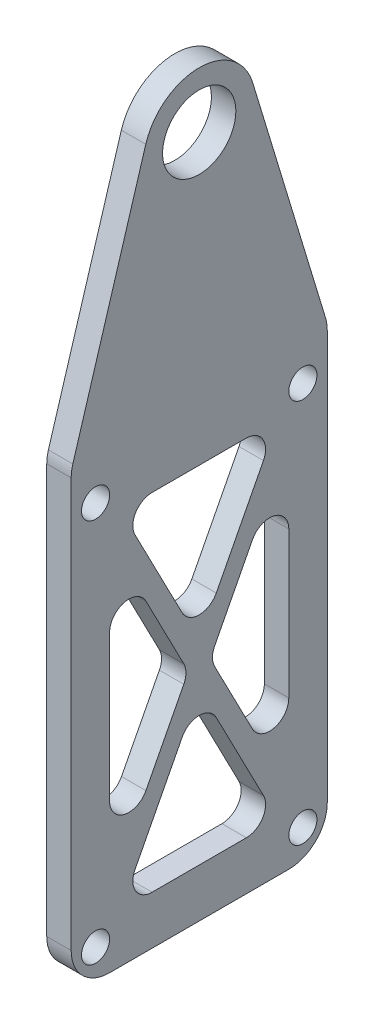
SolidWorks part; units mm, degrees
material "6061 Alloy"
ref_plane "Front Plane" through (0, 0, 0) normal (0, 0, 1) x (1, 0, 0)
ref_plane "Top Plane" through (0, 0, 0) normal (0, 1, 0) x (1, 0, 0)
ref_plane "Right Plane" through (0, 0, 0) normal (1, 0, 0) x (0, 0, -1)
sketch "Sketch1" plane through (0, 0, 0) normal (1, 0, 0) x (0, 0, -1)
  line L0 (-13.4747, 0) -> (13.4747, 0) construction
  line L1 (0, 0) -> (0, 35) construction
  line L2 (-13.4747, 0) -> (0, 35) construction
  line L3 (0, 35) -> (13.4747, 0) construction
  line L4 (13.4747, 0) -> (-13.4747, 0) construction
  line L8 (-13.4747, 0) -> (13.4747, 0) construction
  line L9 (-13.4747, 0) -> (-13.4747, -50) construction
  line L10 (13.4747, 0) -> (13.4747, -50) construction
  line L11 (-13.4747, -50) -> (13.4747, -50) construction
  line L16 (-16.645, -53.81) -> (16.645, -53.81)
  line L17 (-16.645, -53.81) -> (-16.645, 5.15)
  line L18 (16.645, -53.81) -> (16.645, 5.15)
  line L19 (-16.645, 5.15) -> (16.645, 5.15)
  line L20 (-16.645, 5.15) -> (-6.9497, 37.1084)
  line L21 (-6.9497, 37.1084) -> (6.9497, 37.1084) construction
  line L22 (6.9497, 37.1084) -> (16.645, 5.15)
  circle A0 centre (-13.4747, 0) radius 1.8288
  circle A1 centre (0, 35) radius 4.7625
  circle A2 centre (13.4747, 0) radius 1.8288
  circle A3 centre (-13.4747, -50) radius 1.8288
  circle A4 centre (13.4747, -50) radius 1.8288
  arc A5 (-6.9497, 37.1084) -> (6.9497, 37.1084) centre (0, 35) cw
  point P4 (0, 0)
  point P7 (0, -53.81)
  dimension "D3" = 3.6576
  dimension "D4" = 9.525
  dimension "D9" = 2.5
  dimension "D1" = 26.9494
  dimension "D5" = 50
  dimension "D6" = 3.81
  dimension "D7" = 35
  dimension "D8" = 5.15
  dimension "D2" = 33.29
extrude "Boss-Extrude1" add sketch "Sketch1" along normal blind 3.175
sketch "Sketch2" plane through (3.175, 0, 0) normal (1, 0, 0) x (0, 0, -1)
  line L3 (-11.645, -47.5) -> (-11.645, -2.5)
  line L4 (11.645, -47.5) -> (11.645, -2.5)
  line L5 (-11.645, -2.5) -> (11.645, -2.5)
  line L6 (-11.645, -47.5) -> (11.645, -47.5)
  line L7 (-11.645, -47.5) -> (11.645, -2.5) construction
  line L8 (-16.645, -53.81) -> (-16.645, 5.15) construction
  line L15 (11.645, -47.5) -> (-11.645, -2.5) construction
  line L24 (16.645, -53.81) -> (16.645, 5.15) construction
  line L31 (11.645, -44.7805) -> (-10.2375, -2.5)
  line L32 (-10.2375, -47.5) -> (11.645, -5.2195)
  line L33 (10.2375, -47.5) -> (-11.645, -5.2195)
  line L34 (-11.645, -44.7805) -> (10.2375, -2.5)
  line L35 (12.7551, -46.9254) -> (-10.5349, -1.9254) construction
  line L36 (10.5349, -48.0746) -> (-12.7551, -3.0746) construction
  line L37 (-10.5349, -48.0746) -> (12.7551, -3.0746) construction
  line L38 (-12.7551, -46.9254) -> (10.5349, -1.9254) construction
  circle A0 centre (13.4747, -50) radius 1.8288 construction
  circle A1 centre (13.4747, 0) radius 1.8288 construction
  point P0 (11.645, -25)
  point P2 (0, -47.5)
  point P28 (0, -25)
  dimension "D4" = 2.5
  dimension "D1" = 5
  dimension "D2" = 5
  dimension "D3" = 2.5
  dimension "D5" = 1.25
  dimension "D6" = 1.25
extrude "Cut-Extrude1" cut sketch "Sketch2" against normal through all contours L32 L31 L4 | L6 L33 L32 | L3 L34 L33 | L31 L34 L5
fillet "Fillet1" radius 2.5 12 edges at (1.5875, -2.5, -10.2375) (1.5875, -22.2805, 0) (1.5875, -2.5, 10.2375) (1.5875, -5.2195, -11.645) (1.5875, -44.7805, -11.645) (1.5875, -25, -1.4075) (1.5875, -47.5, 10.2375) (1.5875, -47.5, -10.2375) (1.5875, -27.7195, 0) (1.5875, -25, 1.4075) (1.5875, -5.2195, 11.645) (1.5875, -44.7805, 11.645)
fillet "Fillet2" radius 5 4 edges at (1.5875, 5.15, 16.645) (1.5875, 5.15, -16.645) (1.5875, -53.81, -16.645) (1.5875, -53.81, 16.645)
